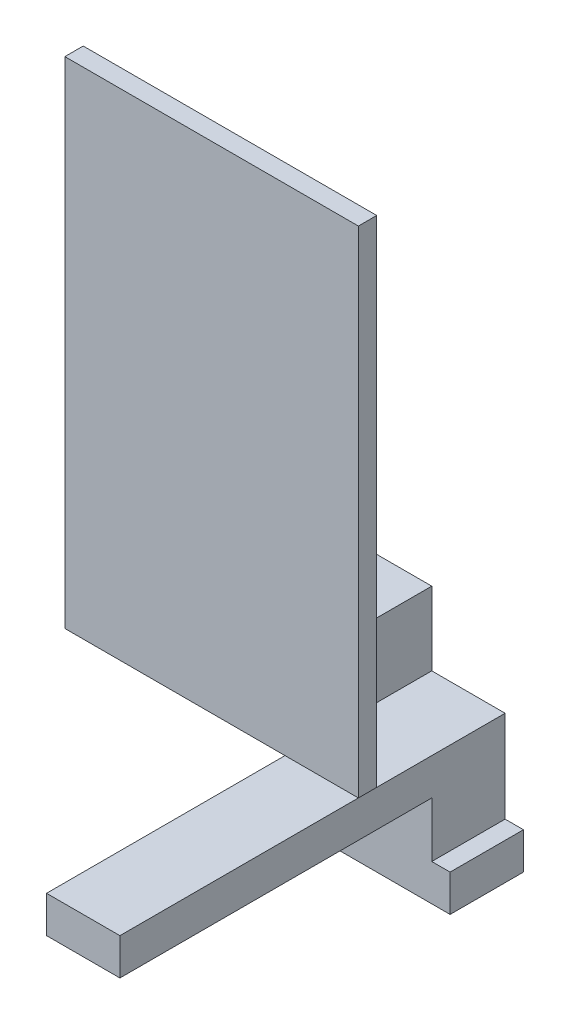
SolidWorks part; units mm, degrees
material "1060 Alloy"
ref_plane "Front Plane" through (0, 0, 0) normal (0, 0, 1) x (1, 0, 0)
ref_plane "Top Plane" through (0, 0, 0) normal (0, 1, 0) x (1, 0, 0)
ref_plane "Right Plane" through (0, 0, 0) normal (1, 0, 0) x (0, 0, -1)
sketch "Sketch1" plane through (0, 0, 0) normal (0, 0, 1) x (1, 0, 0)
  line L0 (0, 0) -> (0, -25) construction
  line L5 (10, 0) -> (-10, 0)
  line L6 (-10, 0) -> (-10, -15)
  line L7 (-10, -15) -> (-15, -15)
  line L8 (-15, -15) -> (-15, -25)
  line L9 (-15, -25) -> (15, -25)
  line L10 (15, -15) -> (15, -25)
  line L11 (10, -15) -> (15, -15)
  line L12 (10, 0) -> (10, -15)
  dimension "D1" = 25
  dimension "D2" = 10
  dimension "D3" = 15
  dimension "D4" = 15
extrude "Boss-Extrude1" add sketch "Sketch1" along normal blind 20
sketch "Sketch2" plane through (0, 0, 0) normal (0, 0, -1) x (-1, 0, 0)
  line L0 (10, 0) -> (40, 0)
  line L1 (40, 0) -> (40, 100)
  line L2 (40, 100) -> (10, 100)
  line L3 (10, 100) -> (10, 10)
  line L4 (-10, 0) -> (-10, 10)
  line L5 (-10, 10) -> (10, 10)
  line L14 (-15, -15) -> (-15, -25)
  line L15 (-15, -25) -> (15, -25)
  line L16 (15, -25) -> (15, -15)
  line L17 (15, -15) -> (10, -15)
  line L18 (10, -15) -> (10, 0)
  line L19 (10, 0) -> (-10, 0)
  line L20 (-10, 0) -> (-10, -15)
  line L21 (-10, -15) -> (-15, -15)
  line L27 (10, 0) -> (-10, 0)
  dimension "D1" = 30
  dimension "D2" = 100
  dimension "D3" = 10
  dimension "D4" = 0
extrude "Boss-Extrude2" add sketch "Sketch2" against normal up to surface (20 mm away) up to face at (0, -13.75, 20)
sketch "Sketch3" plane through (0, 0, 20) normal (0, 0, 1) x (1, 0, 0)
  line L1 (10, 10) -> (-10, 10)
  line L2 (10, 10) -> (10, 0)
  line L3 (10, 0) -> (-10, 0)
  line L4 (-10, 10) -> (-10, 0)
extrude "Boss-Extrude3" add sketch "Sketch3" along normal blind 85
sketch "Sketch6" plane through (0, 0, 20) normal (0, 0, 1) x (1, 0, 0)
  line L0 (-40, 100) -> (-10, 100) construction
  line L1 (-65, 100) -> (15, 100)
  line L2 (-65, 100) -> (-65, 15)
  line L3 (-65, 15) -> (15, 15)
  line L4 (15, 100) -> (15, 15)
  line L5 (10, 10) -> (-10, 10) construction
  line L6 (-10, 100) -> (-10, 10) construction
  line L7 (-40, 0) -> (-40, 100) construction
  dimension "D1" = 5
  dimension "D2" = 25
  dimension "D3" = 25
extrude "Boss-Extrude4" add sketch "Sketch6" along normal blind 25
sketch "Sketch7" plane through (0, 100, 0) normal (0, 1, 0) x (1, 0, 0)
  line L1 (-40, 0) -> (-10, 0)
  line L2 (-40, 0) -> (-40, -20)
  line L3 (-40, -20) -> (-10, -20)
  line L4 (-10, 0) -> (-10, -20)
extrude "Cut-Extrude1" cut sketch "Sketch7" against normal blind 70
sketch "Sketch8" plane through (0, 0, 20) normal (0, 0, -1) x (-1, 0, 0)
  line L8 (40, 30) -> (40, 15)
  line L9 (40, 15) -> (65, 15)
  line L10 (65, 15) -> (65, 100)
  line L11 (65, 100) -> (-15, 100)
  line L12 (-15, 100) -> (-15, 15)
  line L13 (-15, 15) -> (10, 15)
  line L14 (10, 15) -> (10, 30)
  line L15 (10, 30) -> (40, 30)
  line L16 (40, 30) -> (40, 15)
  line L17 (40, 15) -> (65, 15)
  line L18 (65, 15) -> (65, 100)
  line L19 (65, 100) -> (-15, 100)
  line L20 (-15, 100) -> (-15, 15)
  line L21 (-15, 15) -> (10, 15)
  line L22 (10, 15) -> (10, 30)
  line L23 (10, 30) -> (40, 30)
  dimension "D1" = 0
extrude "Cut-Extrude2" cut sketch "Sketch8" against normal blind 20
sketch "Sketch9" plane through (0, 100, 0) normal (0, 1, 0) x (1, 0, 0)
  line L4 (15, -40) -> (-65, -40)
  line L5 (-65, -40) -> (-65, -45)
  line L6 (-65, -45) -> (15, -45)
  line L7 (15, -45) -> (15, -40)
  line L8 (15, -40) -> (-65, -40)
  line L9 (-65, -40) -> (-65, -45)
  line L10 (-65, -45) -> (15, -45)
  line L11 (15, -45) -> (15, -40)
  dimension "D1" = 0
extrude "Boss-Extrude5" add sketch "Sketch9" along normal blind 50
